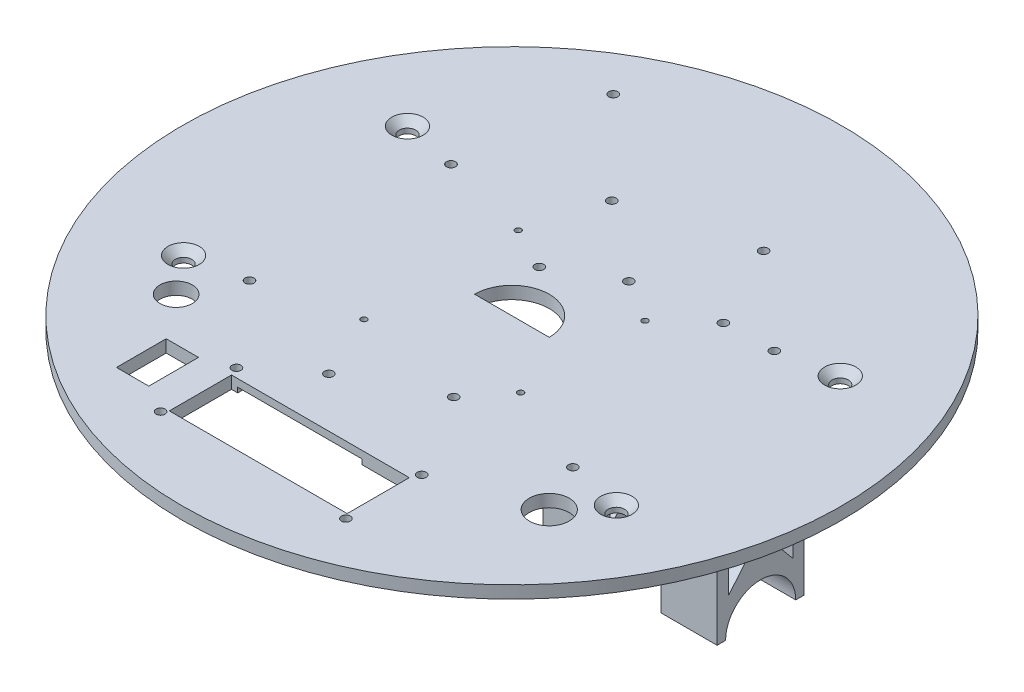
SolidWorks part; units mm, degrees
ref_plane "Alzado" through (0, 0, 0) normal (0, 0, 1) x (1, 0, 0)
ref_plane "Planta" through (0, 0, 0) normal (0, 1, 0) x (1, 0, 0)
ref_plane "Vista lateral" through (0, 0, 0) normal (1, 0, 0) x (0, 0, -1)
sketch "Croquis1" plane through (0, 0, 0) normal (0, 1, 0) x (1, 0, 0)
  circle A0 centre (0, 0) radius 132.5
  dimension "D1" = 265
extrude "Saliente-Extruir1" add sketch "Croquis1" along normal blind 5
sketch "Croquis7" plane through (0, 5, 0) normal (0, 1, 0) x (1, 0, 0)
  line L0 (0, 132.5) -> (0, -132.5) construction
  line L1 (132.5, 0) -> (-132.5, 0) construction
  circle A0 centre (0, 0) radius 132.5 construction
  circle A1 centre (0, 0) radius 132.5 construction
  circle A2 centre (0, 0) radius 132.5 construction
  point P13 (0, 0)
ref_plane "Plano1" through (0, 0, 0) normal (0, 0, 1) x (1, 0, 0)
ref_plane "Plano2" through (0, 0, 0) normal (-1, 0, 0) x (0, 0, 1)
hole_wizard "Avellanado para tornillo con cabeza plana avellanada de M61" positions "Croquis8" profile "Croquis9" countersink size "M6" standard "ISO"
sketch "Croquis8" plane through (0, 5, 0) normal (0, 1, 0) x (1, 0, 0)
  line L0 (0, 145.75) -> (0, -145.75) construction
  line L1 (-114.4, 0) -> (114.4, 0) construction
  line L2 (0, 132.5) -> (0, -132.5) construction
  line L3 (132.5, 0) -> (-132.5, 0) construction
  point P0 (-87, -45)
  point P2 (87, -45)
  point P15 (87, 45)
  point P17 (-87, 45)
  dimension "D1" = 45
  dimension "D2" = 87
  dimension "D3" = 87
  dimension "D4" = 45
sketch "Croquis9" plane through (-87, 5, 45) normal (1, 0, 0) x (0, 0, 1)
  line L0 (0, 0) -> (0, 6.9818)
  line L1 (0, 6.9818) -> (3.3, 4.999)
  line L2 (3.3, 4.999) -> (3.3, 3)
  line L3 (3.3, 3) -> (6.3, 0)
  line L5 (6.3, 0) -> (0, 0)
  line L6 (-3.3, 3) -> (-6.3, 0) construction
  line L10 (0, 6.9818) -> (-3.3, 4.999) construction
  line L11 (0, -6.35) -> (0, 107.95) construction
  dimension "Diámetro de taladro" = 6.6
  dimension "Profundidad de taladro" = 4.999
  dimension "Ángulo de avellanado cercano" = 12.6
  dimension "Ángulo de avellanado lejano" = 90
  dimension "Ángulo de perforador" = 118
hole_wizard "Avellanado para tornillo con cabeza plana avellanada de M21" positions "Croquis10" profile "Croquis11" countersink size "M2" standard "ISO"
sketch "Croquis10" plane through (0, 0, 0) normal (0, -1, 0) x (-1, 0, 0)
  line L2 (0, -145.75) -> (0, 145.75) construction
  line L3 (-114.4, 0) -> (114.4, 0) construction
  point P0 (-28.5, 25)
  point P2 (28.5, 31)
  point P4 (-28.5, -25)
  point P6 (28.5, -31)
  dimension "D1" = 57
  dimension "D2" = 28.5
  dimension "D3" = 50
  dimension "D4" = 62
  dimension "D5" = 25
  dimension "D6" = 31
sketch "Croquis11" plane through (28.5, 0, -25) normal (1, 0, 0) x (0, 0, -1)
  line L0 (0, 0) -> (0, 5.72)
  line L1 (0, 5.72) -> (1.2, 4.999)
  line L2 (1.2, 4.999) -> (1.2, 1)
  line L3 (1.2, 1) -> (2.2, 0)
  line L5 (2.2, 0) -> (0, 0)
  line L6 (-1.2, 1) -> (-2.2, 0) construction
  line L10 (0, 5.72) -> (-1.2, 4.999) construction
  line L11 (0, -6.35) -> (0, 107.95) construction
  dimension "Diámetro de taladro" = 2.4
  dimension "Profundidad de taladro" = 4.999
  dimension "Ángulo de avellanado cercano" = 4.4
  dimension "Ángulo de avellanado lejano" = 90
  dimension "Ángulo de perforador" = 118
sketch "Croquis18" plane through (0, 0, 0) normal (0, -1, 0) x (1, 0, 0)
  line L0 (-15, 0) -> (15, 0)
  arc A0 (-15, 0) -> (15, 0) centre (0, 0) ccw
  dimension "D1" = 30
extrude "Cortar-Extruir1" cut sketch "Croquis18" against normal up to surface (5 mm away) up to face at (28.5, 5, -23.8)
sketch "Croquis20" plane through (0, 0, 0) normal (0, -1, 0) x (1, 0, 0)
  line L0 (0, -132.5) -> (0, 132.5) construction
  line L1 (100, -17.5) -> (30, -17.5)
  line L2 (100, -17.5) -> (100, 17.5)
  line L3 (100, 17.5) -> (30, 17.5)
  line L4 (30, -17.5) -> (30, 17.5)
  line L5 (-30, -17.5) -> (-100, -17.5)
  line L6 (-30, -17.5) -> (-30, 17.5)
  line L7 (-30, 17.5) -> (-100, 17.5)
  line L8 (-100, -17.5) -> (-100, 17.5)
  line L9 (132.5, 0) -> (-132.5, 0) construction
  dimension "D1" = 30
  dimension "D2" = 30
  dimension "D3" = 70
  dimension "D4" = 35
  dimension "D5" = 17.5
extrude "Saliente-Extruir2" add sketch "Croquis20" along normal blind 51
sketch "Croquis21" plane through (100, 0, 0) normal (1, 0, 0) x (0, 0, -1)
  line L0 (17.5, -51) -> (-17.5, -51) construction
  line L1 (-14.1, -51) -> (14.1, -51)
  line L2 (-3, -6) -> (-13, -6)
  line L3 (-13, -6) -> (-13, -36)
  line L5 (-3, -24.0825) -> (-3, -6)
  line L6 (3, -6) -> (3, -24.0825)
  line L8 (13, -36) -> (13, -6)
  line L9 (13, -6) -> (3, -6)
  line L10 (13, -36) -> (3, -24.0825)
  line L11 (-13, -36) -> (-3, -24.0825)
  line L12 (0, 114.4) -> (0, -114.4) construction
  arc A0 (14.1, -51) -> (-14.1, -51) centre (0, -51) ccw
  dimension "D1" = 14.1
  dimension "D2" = 50
  dimension "D3" = 6
  dimension "D4" = 45
  dimension "D5" = 10
  dimension "D6" = 30
  dimension "D7" = 13
extrude "Cortar-Extruir3" cut sketch "Croquis21" against normal up to surface (200 mm away) up to face at (-100, -25.5, 0)
hole_wizard "Taladro de margen para M131" positions "Croquis22" profile "Croquis23" hole size "M13" standard "ISO"
sketch "Croquis22" plane through (0, 5, 0) normal (0, 1, 0) x (1, 0, 0)
  line L0 (-114.4, 0) -> (114.4, 0) construction
  line L2 (0, 132.5) -> (0, -132.5) construction
  point P0 (75, -60)
  dimension "D1" = 60
  dimension "D2" = 75
sketch "Croquis23" plane through (75, 5, 60) normal (1, 0, 0) x (0, 0, 1)
  line L0 (0, 0) -> (0, 9.8059)
  line L1 (0, 9.8059) -> (8, 4.999)
  line L2 (8, 4.999) -> (8, 0)
  line L5 (8, 0) -> (0, 0)
  line L10 (0, 9.8059) -> (-8, 4.999) construction
  line L11 (0, -6.35) -> (0, 107.95) construction
  dimension "Diámetro de taladro" = 16
  dimension "Profundidad de taladro" = 4.999
  dimension "Ángulo de perforador" = 118
sketch "Croquis24" plane through (0, 0, 17.5) normal (0, 0, 1) x (1, 0, 0)
  line L0 (-30, -51) -> (-100, -51) construction
  line L1 (-77.5, -51) -> (-52.5, -51)
  line L2 (-77.5, -51) -> (-77.5, 0)
  line L3 (-77.5, 0) -> (-52.5, 0)
  line L4 (-52.5, -51) -> (-52.5, 0)
  line L5 (-30, 0) -> (-100, 0) construction
  line L6 (100, -51) -> (30, -51) construction
  line L7 (52.5, -51) -> (77.5, -51)
  line L8 (52.5, -51) -> (52.5, 0)
  line L9 (52.5, 0) -> (77.5, 0)
  line L10 (77.5, -51) -> (77.5, 0)
  line L11 (100, 0) -> (30, 0) construction
  line L12 (100, -51) -> (100, 0) construction
  line L13 (30, -51) -> (30, 0) construction
  line L14 (-30, -51) -> (-30, 0) construction
  line L15 (-100, -51) -> (-100, 0) construction
  dimension "D1" = 22.5
  dimension "D2" = 22.5
  dimension "D3" = 22.5
  dimension "D4" = 22.5
extrude "Cortar-Extruir4" cut sketch "Croquis24" against normal up to surface (35 mm away) up to face at (-65, -25.5, -17.5)
chamfer "Chaflán1" distance 3 angle 45 12 edges at (88.75, 0, 17.5) (100, 0, 0) (88.75, 0, -17.5) (41.25, 0, -17.5) (30, 0, 0) (41.25, 0, 17.5) (-41.25, 0, -17.5) (-30, 0, 0) (-41.25, 0, 17.5) (-88.75, 0, -17.5) (-100, 0, 0) (-88.75, 0, 17.5)
sketch "Croquis25" plane through (0, 5, 0) normal (0, 1, 0) x (1, 0, 0)
  line L0 (0, -102) -> (0, -77) construction
  line L1 (-35.75, -102) -> (35.75, -102)
  line L2 (-35.75, -102) -> (-35.75, -77)
  line L3 (-35.75, -77) -> (35.75, -77)
  line L4 (35.75, -102) -> (35.75, -77)
  line L5 (0, 132.5) -> (0, -132.5) construction
  line L6 (132.5, 0) -> (-132.5, 0) construction
  dimension "D3" = 77
  dimension "D1" = 71.5
  dimension "D2" = 25
extrude "Cortar-Extruir5" cut sketch "Croquis25" against normal up to surface (5 mm away) up to face at (39.75, 0, 0)
hole_wizard "Taladro de margen para M31" positions "Croquis16" profile "Croquis17" hole size "M3" standard "ISO"
sketch "Croquis16" plane through (0, 0, 0) normal (0, -1, 0) x (-1, 0, 0)
  line L0 (0, -145.75) -> (0, 145.75) construction
  line L2 (-35.75, -77) -> (35.75, -77) construction
  point P0 (37.25, -104)
  point P2 (-37.25, -104)
  point P4 (37.25, -73.5)
  point P6 (-37.25, -73.5)
  dimension "D1" = 74.5
  dimension "D2" = 30.5
  dimension "D3" = 37.25
  dimension "D4" = 3.5
sketch "Croquis17" plane through (-37.25, 0, 104) normal (1, 0, 0) x (0, 0, -1)
  line L0 (0, 0) -> (0, 6.0805)
  line L1 (0, 6.0805) -> (1.8, 4.999)
  line L2 (1.8, 4.999) -> (1.8, 0)
  line L5 (1.8, 0) -> (0, 0)
  line L10 (0, 6.0805) -> (-1.8, 4.999) construction
  line L11 (0, -6.35) -> (0, 107.95) construction
  dimension "Diámetro de taladro" = 3.6
  dimension "Profundidad de taladro" = 4.999
  dimension "Ángulo de perforador" = 118
sketch "Croquis26" plane through (0, 0, 0) normal (0, -1, 0) x (1, 0, 0)
  line L0 (35.75, 77) -> (35.75, 102) construction
  line L1 (35.75, 99) -> (41.75, 99)
  line L2 (35.75, 99) -> (35.75, 80)
  line L3 (35.75, 80) -> (41.75, 80)
  line L4 (41.75, 99) -> (41.75, 80)
  line L5 (-35.75, 77) -> (35.75, 77) construction
  line L6 (35.75, 102) -> (-35.75, 102) construction
  dimension "D1" = 6
  dimension "D2" = 3
  dimension "D3" = 3
extrude "Cortar-Extruir6" cut sketch "Croquis26" against normal blind 3.5
sketch "Croquis27" plane through (0, 0, 0) normal (0, -1, 0) x (1, 0, 0)
  line L0 (-35.75, 77) -> (35.75, 77) construction
  line L1 (-33.25, 77) -> (16.75, 77)
  line L2 (-33.25, 77) -> (-33.25, 69)
  line L3 (-33.25, 69) -> (16.75, 69)
  line L4 (16.75, 77) -> (16.75, 69)
  line L5 (-35.75, 102) -> (-35.75, 77) construction
  dimension "D1" = 50
  dimension "D2" = 8
  dimension "D3" = 2.5
extrude "Cortar-Extruir7" cut sketch "Croquis27" against normal blind 2
sketch "Croquis28" plane through (0, 0, 0) normal (0, -1, 0) x (1, 0, 0)
  line L0 (-55, 77.5) -> (-55, 97.5) construction
  line L1 (-48.5, 77.5) -> (-61.5, 77.5)
  line L2 (-48.5, 77.5) -> (-48.5, 97.5)
  line L3 (-48.5, 97.5) -> (-61.5, 97.5)
  line L4 (-61.5, 77.5) -> (-61.5, 97.5)
  line L5 (0, -132.5) -> (0, 132.5) construction
  line L7 (-48.5, 87.5) -> (-61.5, 87.5) construction
  line L8 (132.5, 0) -> (-132.5, 0) construction
  dimension "D1" = 20
  dimension "D2" = 13
  dimension "D3" = 55
  dimension "D4" = 87.5
extrude "Cortar-Extruir8" cut sketch "Croquis28" against normal up to surface (5 mm away) up to face at (-37.25, 5, 105.8)
sketch "Croquis29" plane through (0, 5, 0) normal (0, 1, 0) x (1, 0, 0)
  line L0 (132.5, 0) -> (-132.5, 0) construction
  line L3 (0, 132.5) -> (0, -132.5) construction
  circle A2 centre (-75, -60) radius 6.5
  dimension "D1" = 13
  dimension "D3" = 75
  dimension "D2" = 60
extrude "Cortar-Extruir9" cut sketch "Croquis29" against normal up to surface (5 mm away) up to face at (-55, 0, 87.5)
hole_wizard "Avellanado para tornillo con cabeza plana avellanada de M31" positions "Croquis30" profile "Croquis31" countersink size "M3" standard "ISO"
sketch "Croquis30" plane through (0, 0, 0) normal (0, -1, 0) x (-1, 0, 0)
  line L0 (-132.5, 0) -> (132.5, 0) construction
  line L1 (0, 132.5) -> (0, -132.5) construction
  point P0 (65, 40.5)
  point P2 (65, -40.5)
  point P16 (-65, -40.5)
  point P18 (-65, 40.5)
  dimension "D1" = 65
  dimension "D2" = 40.5
  dimension "D3" = 40.5
  dimension "D4" = 65
sketch "Croquis31" plane through (-65, 0, -40.5) normal (1, 0, 0) x (0, 0, -1)
  line L0 (0, 0) -> (0, 6.0805)
  line L1 (0, 6.0805) -> (1.8, 4.999)
  line L2 (1.8, 4.999) -> (1.8, 1.35)
  line L3 (1.8, 1.35) -> (3.15, 0)
  line L5 (3.15, 0) -> (0, 0)
  line L6 (-1.8, 1.35) -> (-3.15, 0) construction
  line L10 (0, 6.0805) -> (-1.8, 4.999) construction
  line L11 (0, -6.35) -> (0, 107.95) construction
  dimension "Diámetro de taladro" = 3.6
  dimension "Profundidad de taladro" = 4.999
  dimension "Ángulo de avellanado cercano" = 6.3
  dimension "Ángulo de avellanado lejano" = 90
  dimension "Ángulo de perforador" = 118
hole_wizard "Avellanado para tornillo con cabeza plana avellanada de M32" positions "Croquis32" profile "Croquis33" countersink size "M3" standard "ISO"
sketch "Croquis32" plane through (0, 0, 0) normal (0, -1, 0) x (-1, 0, 0)
  line L0 (-132.5, 0) -> (132.5, 0) construction
  line L1 (0, 132.5) -> (0, -132.5) construction
  point P0 (56.74, 97.5)
  point P2 (20, 60.12)
  dimension "D1" = 36.74
  dimension "D2" = 37.38
  dimension "D3" = 97.5
  dimension "D4" = 20
sketch "Croquis33" plane through (-56.74, 0, -97.5) normal (1, 0, 0) x (0, 0, -1)
  line L0 (0, 0) -> (0, 6.0805)
  line L1 (0, 6.0805) -> (1.8, 4.999)
  line L2 (1.8, 4.999) -> (1.8, 1.35)
  line L3 (1.8, 1.35) -> (3.15, 0)
  line L5 (3.15, 0) -> (0, 0)
  line L6 (-1.8, 1.35) -> (-3.15, 0) construction
  line L10 (0, 6.0805) -> (-1.8, 4.999) construction
  line L11 (0, -6.35) -> (0, 107.95) construction
  dimension "Diámetro de taladro" = 3.6
  dimension "Profundidad de taladro" = 4.999
  dimension "Ángulo de avellanado cercano" = 6.3
  dimension "Ángulo de avellanado lejano" = 90
  dimension "Ángulo de perforador" = 118
hole_wizard "Avellanado para tornillo con cabeza plana avellanada de M33" positions "Croquis35" profile "Croquis36" countersink size "M3" standard "ISO"
sketch "Croquis35" plane through (0, 0, 0) normal (0, -1, 0) x (-1, 0, 0)
  line L0 (0, 132.5) -> (0, -132.5) construction
  line L1 (-132.5, 0) -> (132.5, 0) construction
  point P0 (-28, 73.18)
  point P2 (-45, 40)
  dimension "D1" = 17
  dimension "D2" = 33.18
  dimension "D3" = 45
  dimension "D4" = 40
sketch "Croquis36" plane through (28, 0, -73.18) normal (1, 0, 0) x (0, 0, -1)
  line L0 (0, 0) -> (0, 6.0805)
  line L1 (0, 6.0805) -> (1.8, 4.999)
  line L2 (1.8, 4.999) -> (1.8, 1.35)
  line L3 (1.8, 1.35) -> (3.15, 0)
  line L5 (3.15, 0) -> (0, 0)
  line L6 (-1.8, 1.35) -> (-3.15, 0) construction
  line L10 (0, 6.0805) -> (-1.8, 4.999) construction
  line L11 (0, -6.35) -> (0, 107.95) construction
  dimension "Diámetro de taladro" = 3.6
  dimension "Profundidad de taladro" = 4.999
  dimension "Ángulo de avellanado cercano" = 6.3
  dimension "Ángulo de avellanado lejano" = 90
  dimension "Ángulo de perforador" = 118
hole_wizard "Avellanado para tornillo con cabeza plana avellanada de M34" positions "Croquis37" profile "Croquis38" countersink size "M3" standard "ISO"
sketch "Croquis37" plane through (0, 0, 0) normal (0, -1, 0) x (-1, 0, 0)
  line L0 (0, 132.5) -> (0, -132.5) construction
  line L1 (-132.5, 0) -> (132.5, 0) construction
  point P0 (16.59, -57)
  point P2 (-16.59, -40)
  dimension "D1" = 33.18
  dimension "D2" = 17
  dimension "D3" = 16.59
  dimension "D4" = 40
sketch "Croquis38" plane through (-16.59, 0, 57) normal (1, 0, 0) x (0, 0, -1)
  line L0 (0, 0) -> (0, 6.0805)
  line L1 (0, 6.0805) -> (1.8, 4.999)
  line L2 (1.8, 4.999) -> (1.8, 1.35)
  line L3 (1.8, 1.35) -> (3.15, 0)
  line L5 (3.15, 0) -> (0, 0)
  line L6 (-1.8, 1.35) -> (-3.15, 0) construction
  line L10 (0, 6.0805) -> (-1.8, 4.999) construction
  line L11 (0, -6.35) -> (0, 107.95) construction
  dimension "Diámetro de taladro" = 3.6
  dimension "Profundidad de taladro" = 4.999
  dimension "Ángulo de avellanado cercano" = 6.3
  dimension "Ángulo de avellanado lejano" = 90
  dimension "Ángulo de perforador" = 118
hole_wizard "Avellanado para tornillo con cabeza plana avellanada de M35" positions "Croquis39" profile "Croquis40" countersink size "M3" standard "ISO"
sketch "Croquis39" plane through (0, 0, 0) normal (0, -1, 0) x (-1, 0, 0)
  line L0 (0, 132.5) -> (0, -132.5) construction
  line L1 (-132.5, 0) -> (132.5, 0) construction
  point P0 (11.5, 22.5)
  point P2 (-11.5, 35.5)
  dimension "D1" = 13
  dimension "D2" = 23
  dimension "D3" = 11.5
  dimension "D4" = 22.5
sketch "Croquis40" plane through (-11.5, 0, -22.5) normal (1, 0, 0) x (0, 0, -1)
  line L0 (0, 0) -> (0, 6.0805)
  line L1 (0, 6.0805) -> (1.8, 4.999)
  line L2 (1.8, 4.999) -> (1.8, 1.35)
  line L3 (1.8, 1.35) -> (3.15, 0)
  line L5 (3.15, 0) -> (0, 0)
  line L6 (-1.8, 1.35) -> (-3.15, 0) construction
  line L10 (0, 6.0805) -> (-1.8, 4.999) construction
  line L11 (0, -6.35) -> (0, 107.95) construction
  dimension "Diámetro de taladro" = 3.6
  dimension "Profundidad de taladro" = 4.999
  dimension "Ángulo de avellanado cercano" = 6.3
  dimension "Ángulo de avellanado lejano" = 90
  dimension "Ángulo de perforador" = 118
sketch "Croquis41" plane through (0, 0, 0) normal (0, -1, 0) x (-1, 0, 0)
  line L0 (-114.4, 0) -> (114.4, 0) construction
  line L1 (0, -145.75) -> (0, 145.75) construction
  circle A0 centre (7.753, -5.24) radius 3.75
  circle A1 centre (-7.807, -5.24) radius 3.75
  dimension "D1" = 7.5
  dimension "D2" = 15.56
  dimension "D3" = 5.24
  dimension "D4" = 7.753
extrude "Saliente-Extruir3" add sketch "Croquis41" along normal blind 15 contours A0 | A1
sketch "Croquis42" plane through (0, -15, 0) normal (0, -1, 0) x (-1, 0, 0)
  circle A0 centre (7.753, -5.24) radius 2
  circle A1 centre (-7.807, -5.24) radius 2
  circle A2 centre (7.753, -5.24) radius 3.75 construction
  circle A3 centre (-7.807, -5.24) radius 3.75 construction
  dimension "D1" = 4
extrude "Cortar-Extruir10" cut sketch "Croquis42" against normal blind 6.5
